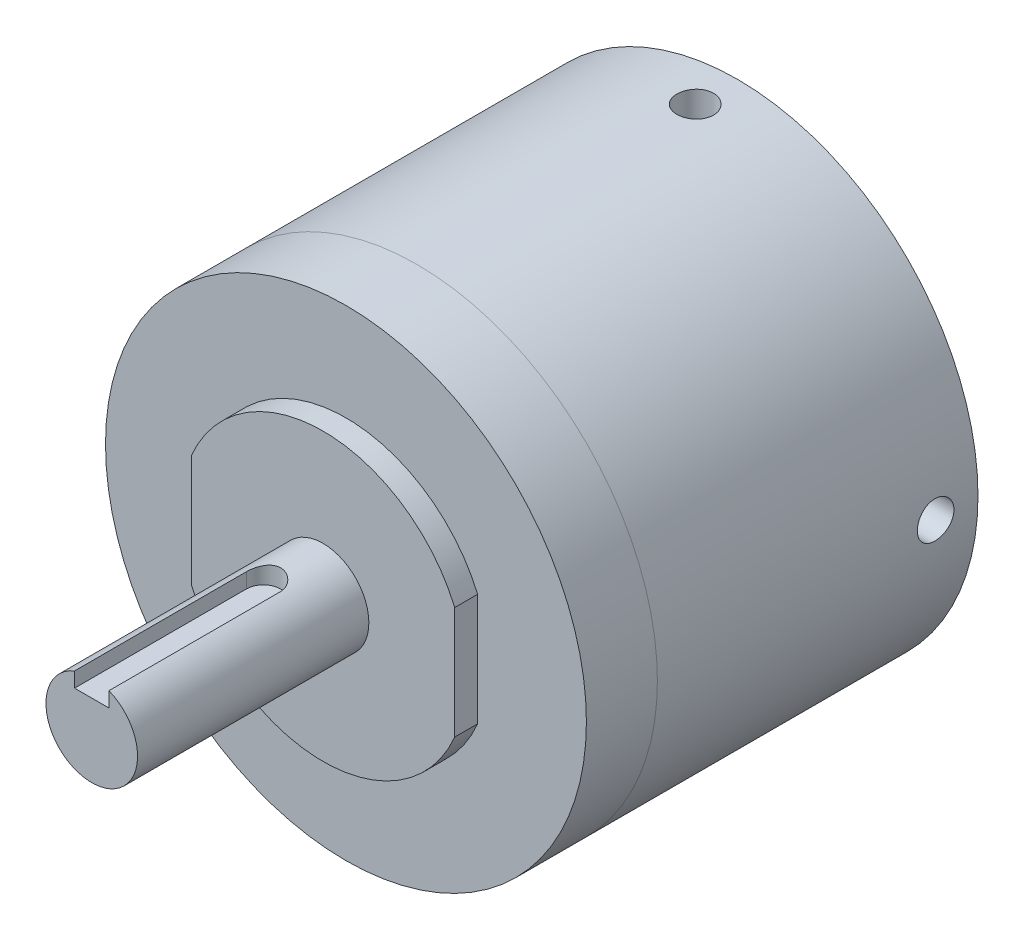
SolidWorks part; units mm, degrees
ref_plane "正面" through (0, 0, 0) normal (0, 0, 1) x (1, 0, 0)
ref_plane "平面" through (0, 0, 0) normal (0, 1, 0) x (1, 0, 0)
ref_plane "右側面" through (0, 0, 0) normal (1, 0, 0) x (0, 0, -1)
sketch "ｽｹｯﾁ1" plane through (0, 0, 0) normal (0, 0, 1) x (1, 0, 0)
  circle A0 centre (0, 0) radius 21
  circle A1 centre (0, 0) radius 17.75
  dimension "D1" = 42
  dimension "D2" = 35.5
extrude "ﾎﾞｽ - 押し出し1" add sketch "ｽｹｯﾁ1" along normal blind 34.2
sketch "ｽｹｯﾁ2" plane through (0, 0, 34.2) normal (0, 0, 1) x (1, 0, 0)
  circle A0 centre (0, 0) radius 21 construction
  circle A1 centre (0, 0) radius 21
extrude "ﾎﾞｽ - 押し出し2" add sketch "ｽｹｯﾁ2" against normal blind 12.2
sketch "ｽｹｯﾁ3" plane through (0, 0, 34.2) normal (0, 0, 1) x (1, 0, 0)
  line L0 (-11.5, -4.899) -> (-11.5, 4.899)
  line L1 (11.5, 4.899) -> (11.5, -4.899)
  arc A0 (-11.5, -4.899) -> (11.5, -4.899) centre (0, 0) ccw
  arc A2 (11.5, 4.899) -> (-11.5, 4.899) centre (0, 0) ccw
  dimension "D1" = 25
  dimension "D2" = 23
extrude "ﾎﾞｽ - 押し出し3" add sketch "ｽｹｯﾁ3" along normal blind 2
sketch "ｽｹｯﾁ4" plane through (0, 0, 36.2) normal (0, 0, 1) x (1, 0, 0)
  circle A0 centre (0, 0) radius 4
  dimension "D1" = 8
extrude "ﾎﾞｽ - 押し出し4" add sketch "ｽｹｯﾁ4" along normal blind 20.2
sketch "ｽｹｯﾁ5" plane through (0, 0, 0) normal (0, 1, 0) x (1, 0, 0)
  line L0 (0, 0) -> (0, -56.4) construction
  line L1 (-4, -56.4) -> (4, -56.4) construction
  line L2 (17.75, 0) -> (-17.75, 0) construction
  circle A0 centre (0, -3.7) radius 1.6
  dimension "D1" = 3.7
  dimension "D2" = 3.2
extrude "ｶｯﾄ - 押し出し1" cut sketch "ｽｹｯﾁ5" against normal through all
ref_axis "軸1" through (0, 0, 34.2) along (0, 0, -1)
pattern_circular "円形ﾊﾟﾀｰﾝ1" count 4 over 360 about axis through (0, 0, 34.2) along (0, 0, -1) of "ｶｯﾄ - 押し出し1"
ref_plane "平面1" through (0, 4, 0) normal (0, 1, 0) x (1, 0, 0)
sketch "ｽｹｯﾁ7" plane through (0, 4, 0) normal (0, 1, 0) x (1, 0, 0)
  line L0 (0, -56.4) -> (0, -41.4) construction
  line L1 (-4, -56.4) -> (4, -56.4) construction
  line L2 (-1.5, -56.4) -> (-1.5, -41.4)
  line L3 (1.5, -56.4) -> (1.5, -41.4)
  arc A0 (-1.5, -56.4) -> (1.5, -56.4) centre (0, -56.4) ccw
  arc A1 (1.5, -41.4) -> (-1.5, -41.4) centre (0, -41.4) ccw
  point P4 (0, -48.9)
  dimension "D1" = 1.5
  dimension "D2" = 15
extrude "ｶｯﾄ - 押し出し2" cut sketch "ｽｹｯﾁ7" against normal blind 1.6
ref_plane "平面2" through (0, 21, 0) normal (0, 1, 0) x (1, 0, 0)
sketch "ｽｹｯﾁ8" plane through (0, 21, 0) normal (0, 1, 0) x (1, 0, 0)
  line L0 (-21, -28) -> (21, -28)
  line L1 (-21, -5.3) -> (-21, -34.2) construction
  line L2 (21, -34.2) -> (21, -5.2999) construction
  line L3 (17.75, 0) -> (-17.75, 0) construction
  dimension "D1" = 28
split line "分割ﾗｲﾝ1"
